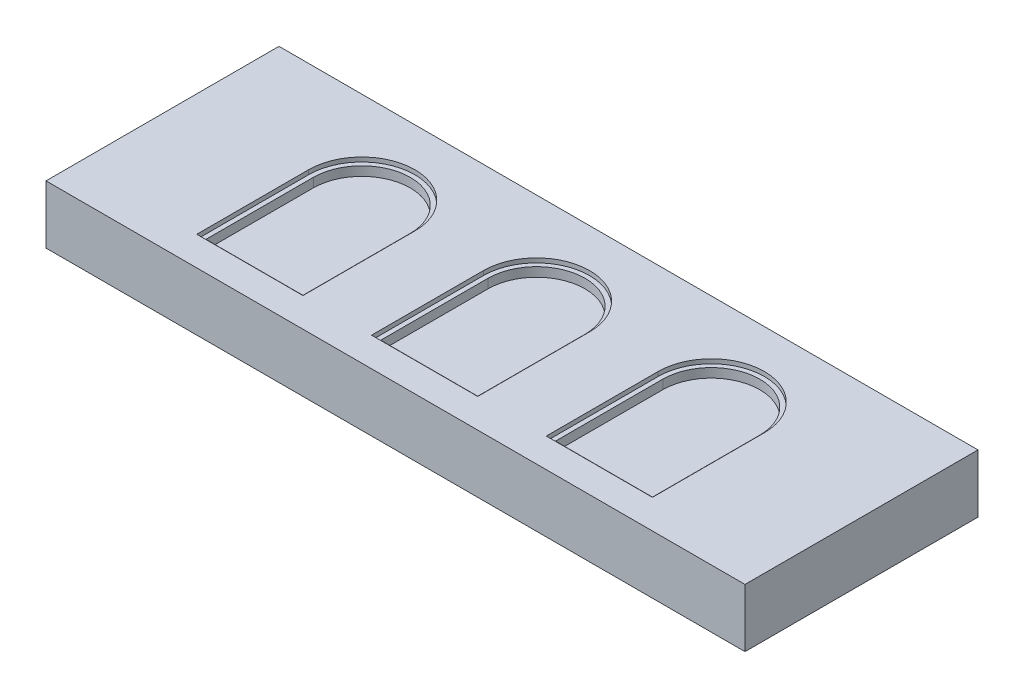
SolidWorks part; units mm, degrees
ref_plane "Front Plane" through (0, 0, 0) normal (0, 0, 1) x (1, 0, 0)
ref_plane "Top Plane" through (0, 0, 0) normal (0, 1, 0) x (1, 0, 0)
ref_plane "Right Plane" through (0, 0, 0) normal (1, 0, 0) x (0, 0, -1)
sketch "Sketch1" plane through (0, 0, 0) normal (0, 1, 0) x (1, 0, 0)
  line L1 (0, 0) -> (152.4, 0)
  line L2 (0, 0) -> (0, 50.8)
  line L3 (0, 50.8) -> (152.4, 50.8)
  line L4 (152.4, 0) -> (152.4, 50.8)
extrude "Boss-Extrude1" add sketch "Sketch1" along normal blind 12.7
sketch "Sketch2" plane through (0, 12.7, 0) normal (0, 1, 0) x (1, 0, 0)
  line L0 (64.627, 30.75) -> (64.627, 6.35)
  line L1 (64.627, 6.35) -> (87.773, 6.35)
  line L2 (87.773, 6.35) -> (87.773, 30.75)
  line L3 (0, 0) -> (152.4, 0) construction
  arc A0 (87.773, 30.75) -> (64.627, 30.75) centre (76.2, 30.75) ccw
  point P5 (76.2, 6.35)
  point P8 (76.2, 0)
  dimension "D1" = 23.146
  dimension "D2" = 24.4
  dimension "D3" = 6.35
extrude "Cut-Extrude1" cut sketch "Sketch2" against normal blind 0.95
sketch "Sketch3" plane through (0, 11.75, 0) normal (0, 1, 0) x (1, 0, 0)
  line L9 (65.627, 30.75) -> (65.627, 7.35)
  line L10 (65.627, 7.35) -> (86.773, 7.35)
  line L11 (86.773, 7.35) -> (86.773, 30.75)
  line L12 (65.627, 30.75) -> (65.627, 7.35)
  line L13 (65.627, 7.35) -> (86.773, 7.35)
  line L14 (86.773, 7.35) -> (86.773, 30.75)
  arc A3 (86.773, 30.75) -> (65.627, 30.75) centre (76.2, 30.75) ccw
  arc A4 (86.773, 30.75) -> (65.627, 30.75) centre (76.2, 30.75) ccw
  dimension "D1" = 1
extrude "Cut-Extrude2" cut sketch "Sketch3" against normal blind 2
pattern_linear "LPattern1" count 2 spacing 38.1 along (1, 0, 0) count 2 spacing 38.1 along (-1, 0, 0) of "Cut-Extrude2", "Cut-Extrude1"
